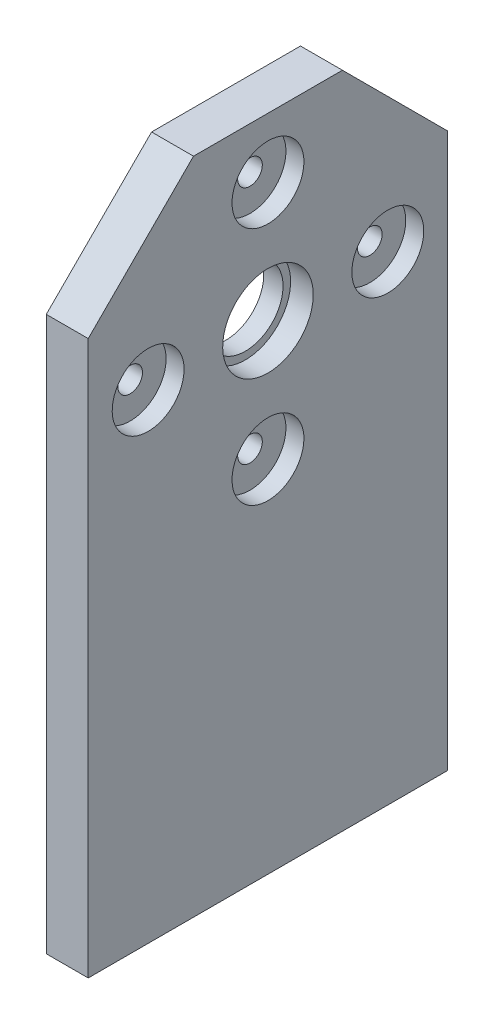
SolidWorks part; units mm, degrees
material "ASTM A36 Steel"
ref_plane "Front Plane" through (0, 0, 0) normal (0, 0, 1) x (1, 0, 0)
ref_plane "Top Plane" through (0, 0, 0) normal (0, 1, 0) x (1, 0, 0)
ref_plane "Right Plane" through (0, 0, 0) normal (1, 0, 0) x (0, 0, -1)
sketch "Sketch1" plane through (-18.0375, 0, 0) normal (1, 0, 0) x (0, 0, -1)
  line L0 (-47.625, -127) -> (-47.625, 19.7269)
  line L1 (47.625, 19.7269) -> (47.625, -127)
  line L2 (47.625, -127) -> (-47.625, -127)
  line L3 (-47.625, 19.7269) -> (-19.7269, 47.625)
  line L4 (-19.7269, 47.625) -> (19.7269, 47.625)
  line L5 (19.7269, 47.625) -> (47.625, 19.7269)
  line L6 (0, 0) -> (33.676, 33.676) construction
  line L7 (0, 47.625) -> (0, 0) construction
  line L8 (0, 0) -> (-33.676, 33.676) construction
  point P10 (-47.625, 31.0325)
  dimension "D1" = 45
  dimension "D2" = 95.25
  dimension "D3" = 127
extrude "Boss-Extrude1" add sketch "Sketch1" against normal up to surface (11.1125 mm away)
sketch "Sketch2" plane through (-18.0375, 0, 0) normal (1, 0, 0) x (0, 0, -1)
  circle A0 centre (0, 0) radius 12
  dimension "D1" = 24
extrude "Cut-Extrude1" cut sketch "Sketch2" against normal blind 6
sketch "Sketch3" plane through (-24.0375, 0, 0) normal (1, 0, 0) x (0, 0, -1)
  circle A0 centre (0, 0) radius 10
  dimension "D1" = 20
extrude "Cut-Extrude2" cut sketch "Sketch3" against normal through all
sketch "Sketch4" plane through (-29.15, 0, 0) normal (-1, 0, 0) x (0, 0, 1)
  circle A0 centre (0, -31.75) radius 3.2639
  circle A1 centre (31.75, 0) radius 3.2639
  circle A2 centre (-31.75, 0) radius 3.2639
  circle A3 centre (0, 31.75) radius 3.2639
  dimension "D1" = 6.5278
extrude "Cut-Extrude3" cut sketch "Sketch4" against normal through all
sketch "Sketch5" plane through (-18.0375, 0, 0) normal (1, 0, 0) x (0, 0, -1)
  circle A0 centre (-31.75, 0) radius 9.525
  circle A1 centre (0, 31.75) radius 9.525
  circle A2 centre (31.75, 0) radius 9.525
  circle A3 centre (0, -31.75) radius 9.525
  dimension "D1" = 19.05
extrude "Cut-Extrude4" cut sketch "Sketch5" against normal offset from surface (4.7625 mm away) 6.35 up to face at (-29.15, -31.75, 3.2639)
sketch "Sketch6" plane through (0, -127, 0) normal (0, -1, 0) x (1, 0, 0)
  line L0 (-29.15, 47.625) -> (-18.0375, -47.625) construction
  line L1 (-23.5937, -38.1) -> (-23.5937, 38.1) construction
  circle A0 centre (-23.5937, 0) radius 2.7781
  circle A1 centre (-23.5937, 38.1) radius 2.7781
  circle A2 centre (-23.5937, -38.1) radius 2.7781
  point P7 (-23.5937, 0)
  dimension "D1" = 5.5562
  dimension "D2" = 76.2
extrude "Cut-Extrude5" cut sketch "Sketch6" against normal blind 38.1
